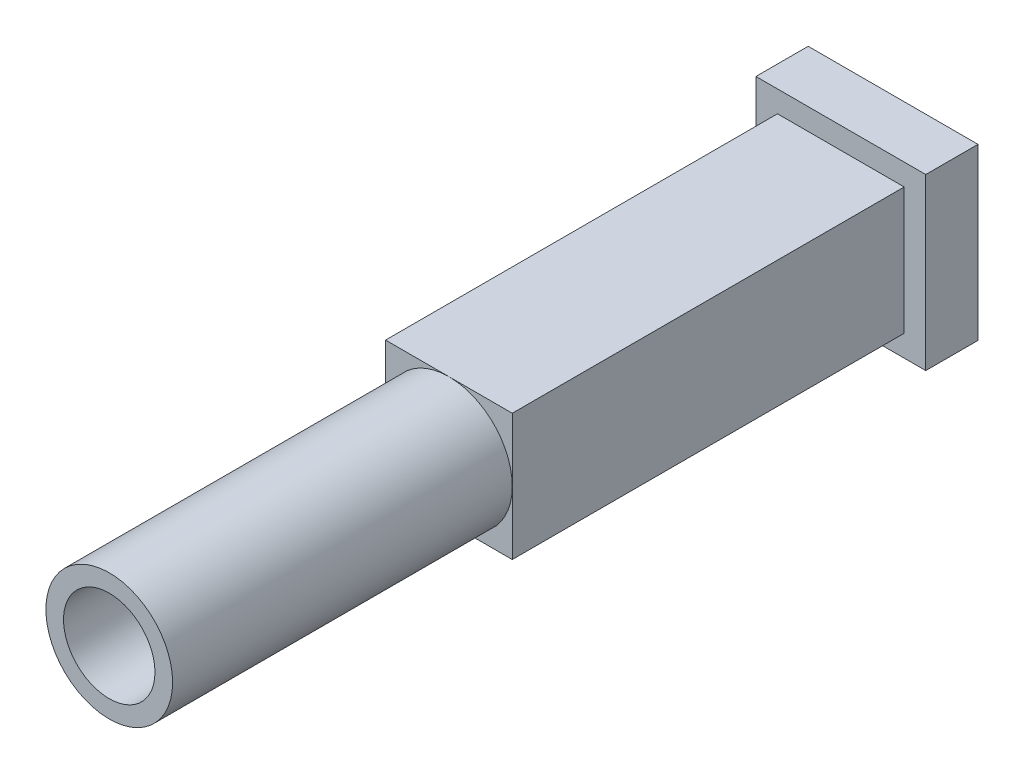
SolidWorks part; units mm, degrees
ref_plane "Front Plane" through (0, 0, 0) normal (0, 0, 1) x (1, 0, 0)
ref_plane "Top Plane" through (0, 0, 0) normal (0, 1, 0) x (1, 0, 0)
ref_plane "Right Plane" through (0, 0, 0) normal (1, 0, 0) x (0, 0, -1)
sketch "Sketch1" plane through (0, 0, 0) normal (0, 0, 1) x (1, 0, 0)
  line L1 (0, 0) -> (9.7, 0)
  line L2 (0, 0) -> (0, -9.7)
  line L3 (0, -9.7) -> (9.7, -9.7)
  line L4 (9.7, 0) -> (9.7, -9.7)
  dimension "D1" = 9.7
extrude "Boss-Extrude1" add sketch "Sketch1" along normal blind 30
sketch "Sketch2" plane through (0, 0, 30) normal (0, 0, 1) x (1, 0, 0)
  line L0 (9.7, 0) -> (0, 0) construction
  line L1 (0, 0) -> (0, -9.7) construction
  line L2 (9.7, -9.7) -> (9.7, 0) construction
  circle A0 centre (4.85, -4.85) radius 4.85
extrude "Boss-Extrude2" add sketch "Sketch2" along normal blind 26
sketch "Sketch3" plane through (0, 0, 0) normal (0, 0, -1) x (-1, 0, 0)
  line L0 (-11.35, 1.65) -> (1.65, -11.35) construction
  line L1 (-11.35, 1.65) -> (1.65, 1.65)
  line L2 (-11.35, 1.65) -> (-11.35, -11.35)
  line L3 (-11.35, -11.35) -> (1.65, -11.35)
  line L4 (1.65, 1.65) -> (1.65, -11.35)
  line L5 (-9.7, -9.7) -> (0, 0) construction
  point P8 (-4.85, -4.85)
  point P9 (-4.85, -4.85)
  dimension "D1" = 13
extrude "Boss-Extrude3" add sketch "Sketch3" along normal blind 4 contours L1 L4 L3 L2
sketch "Sketch4" plane through (0, 0, 56) normal (0, 0, 1) x (1, 0, 0)
  circle A0 centre (4.85, -4.85) radius 3.5
  dimension "D1" = 7
extrude "Cut-Extrude1" cut sketch "Sketch4" against normal blind 10
